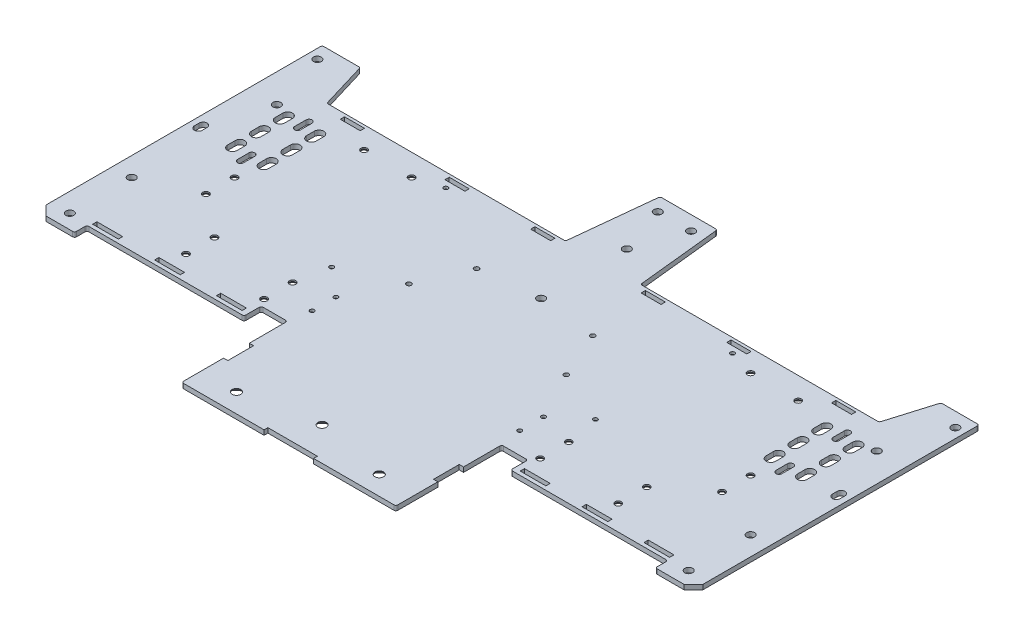
SolidWorks part; units mm, degrees
material "Титан"
ref_plane "Спереди" through (0, 0, 0) normal (0, 0, 1) x (1, 0, 0)
ref_plane "Сверху" through (0, 0, 0) normal (0, 1, 0) x (1, 0, 0)
ref_plane "Справа" through (0, 0, 0) normal (1, 0, 0) x (0, 0, -1)
sketch "Эскиз2" plane through (0, 0, 0) normal (0, 1, 0) x (1, 0, 0)
  line L9 (0, 240.5865) -> (0, -896.1011) construction
  line L10 (112.5, -237) -> (112.5, -330)
  line L11 (112.5, -330) -> (-112.5, -330)
  line L13 (-112.5, -237) -> (-112.5, -330)
  line L14 (-345, -237) -> (-112.5, -237)
  line L30 (-345, -237) -> (-345, 50)
  line L31 (-345, 50) -> (-305, 50)
  line L32 (-305, 50) -> (-290, 0)
  line L33 (-290, 0) -> (290, 0)
  line L34 (305, 50) -> (290, 0)
  line L35 (345, 50) -> (305, 50)
  line L39 (345, -237) -> (345, 50)
  line L40 (112.5, -237) -> (345, -237)
  dimension "D2" = 690
  dimension "D4" = 50
  dimension "D5" = 580
  dimension "D6" = 40
  dimension "D7" = 330
  dimension "D8" = 93
  dimension "D10" = 225
extrude "Бобышка-Вытянуть1" add sketch "Эскиз2" along normal blind 5
sketch "Эскиз21" plane through (0, 5, 0) normal (0, 1, 0) x (1, 0, 0)
  line L0 (-39.4594, 0) -> (-30, 90)
  line L1 (290, 0) -> (-290, 0) construction
  line L2 (0, 0) -> (0, -50000) construction
  line L3 (39.4594, 0) -> (30, 90)
  line L4 (-30, 90) -> (30, 90)
  line L5 (-39.4594, 0) -> (39.4594, 0)
  dimension "D1" = 90
  dimension "D2" = 12
  dimension "D3" = 60
extrude "Бобышка-Вытянуть2" add sketch "Эскиз21" against normal blind 5
sketch "Эскиз22" plane through (0, 5, 0) normal (0, 1, 0) x (1, 0, 0)
  line L0 (0, 0) -> (0, -50000) construction
  line L1 (-345, -237) -> (-305, -237)
  line L2 (-345, -237) -> (-345, -250)
  line L3 (-345, -250) -> (-305, -250)
  line L4 (-305, -237) -> (-305, -250)
  line L5 (305, -237) -> (305, -250)
  line L6 (345, -250) -> (305, -250)
  line L7 (345, -237) -> (345, -250)
  line L8 (345, -237) -> (305, -237)
  line L9 (-345, -237) -> (-112.5, -237) construction
  dimension "D1" = 40
  dimension "D2" = 13
extrude "Бобышка-Вытянуть3" add sketch "Эскиз22" against normal blind 5
sketch "Эскиз8" plane through (0, 5, 0) normal (0, 1, 0) x (1, 0, 0)
  line L0 (-39.4594, 0) -> (-290, 0) construction
  line L3 (-266.25, -40) -> (-266.25, -32) construction
  line L6 (-271.25, -40) -> (-271.25, -32)
  line L9 (-261.25, -40) -> (-261.25, -32)
  line L12 (-266.25, -65) -> (-266.25, -57) construction
  line L19 (-271.25, -65) -> (-271.25, -57)
  line L22 (-261.25, -65) -> (-261.25, -57)
  line L25 (-266.25, -90) -> (-266.25, -82) construction
  line L26 (0, 0) -> (0, -50000) construction
  line L29 (-271.25, -90) -> (-271.25, -82)
  line L38 (-261.25, -90) -> (-261.25, -82)
  line L45 (-299.25, -65) -> (-299.25, -57) construction
  line L46 (-304.25, -65) -> (-304.25, -57)
  line L49 (-299.25, -40) -> (-299.25, -32) construction
  line L50 (-304.25, -40) -> (-304.25, -32)
  line L51 (-294.25, -40) -> (-294.25, -32)
  line L52 (-294.25, -65) -> (-294.25, -57)
  line L53 (-299.25, -90) -> (-299.25, -82) construction
  line L54 (-304.25, -90) -> (-304.25, -82)
  line L55 (-294.25, -90) -> (-294.25, -82)
  line L56 (266.25, -40) -> (266.25, -32) construction
  line L57 (271.25, -40) -> (271.25, -32)
  line L58 (261.25, -40) -> (261.25, -32)
  line L59 (266.25, -65) -> (266.25, -57) construction
  line L60 (271.25, -65) -> (271.25, -57)
  line L61 (261.25, -65) -> (261.25, -57)
  line L62 (266.25, -90) -> (266.25, -82) construction
  line L63 (271.25, -90) -> (271.25, -82)
  line L64 (261.25, -90) -> (261.25, -82)
  line L65 (299.25, -65) -> (299.25, -57) construction
  line L66 (304.25, -65) -> (304.25, -57)
  line L67 (294.25, -65) -> (294.25, -57)
  line L68 (299.25, -40) -> (299.25, -32) construction
  line L69 (304.25, -40) -> (304.25, -32)
  line L70 (294.25, -40) -> (294.25, -32)
  line L71 (299.25, -90) -> (299.25, -82) construction
  line L72 (304.25, -90) -> (304.25, -82)
  line L73 (294.25, -90) -> (294.25, -82)
  arc A36 (-304.25, -40) -> (-294.25, -40) centre (-299.25, -40) ccw
  arc A37 (-294.25, -32) -> (-304.25, -32) centre (-299.25, -32) ccw
  arc A38 (-271.25, -40) -> (-261.25, -40) centre (-266.25, -40) ccw
  arc A39 (-261.25, -32) -> (-271.25, -32) centre (-266.25, -32) ccw
  arc A40 (-271.25, -65) -> (-261.25, -65) centre (-266.25, -65) ccw
  arc A41 (-261.25, -57) -> (-271.25, -57) centre (-266.25, -57) ccw
  arc A42 (-271.25, -90) -> (-261.25, -90) centre (-266.25, -90) ccw
  arc A43 (-261.25, -82) -> (-271.25, -82) centre (-266.25, -82) ccw
  arc A44 (-304.25, -65) -> (-294.25, -65) centre (-299.25, -65) ccw
  arc A45 (-294.25, -57) -> (-304.25, -57) centre (-299.25, -57) ccw
  arc A46 (-304.25, -90) -> (-294.25, -90) centre (-299.25, -90) ccw
  arc A47 (-294.25, -82) -> (-304.25, -82) centre (-299.25, -82) ccw
  arc A48 (271.25, -40) -> (261.25, -40) centre (266.25, -40) cw
  arc A49 (261.25, -32) -> (271.25, -32) centre (266.25, -32) cw
  arc A50 (271.25, -65) -> (261.25, -65) centre (266.25, -65) cw
  arc A51 (261.25, -57) -> (271.25, -57) centre (266.25, -57) cw
  arc A52 (271.25, -90) -> (261.25, -90) centre (266.25, -90) cw
  arc A53 (261.25, -82) -> (271.25, -82) centre (266.25, -82) cw
  arc A54 (304.25, -65) -> (294.25, -65) centre (299.25, -65) cw
  arc A55 (294.25, -57) -> (304.25, -57) centre (299.25, -57) cw
  arc A56 (304.25, -40) -> (294.25, -40) centre (299.25, -40) cw
  arc A57 (294.25, -32) -> (304.25, -32) centre (299.25, -32) cw
  arc A58 (304.25, -90) -> (294.25, -90) centre (299.25, -90) cw
  arc A59 (294.25, -82) -> (304.25, -82) centre (299.25, -82) cw
  point P4 (266.25, -36)
  point P7 (-266.25, -36)
  point P14 (-266.25, -61)
  point P21 (-266.25, -86)
  point P28 (-299.25, -61)
  point P35 (-299.25, -86)
  point P48 (266.25, -61)
  point P55 (266.25, -86)
  point P62 (299.25, -61)
  point P69 (-299.25, -36)
  point P76 (299.25, -36)
  point P83 (299.25, -86)
  dimension "D2" = 8
  dimension "D1" = 10
  dimension "D3" = 598.5
  dimension "D4" = 36
  dimension "D5" = 2
  dimension "D6" = 3
  dimension "D7" = 33
extrude "Вырез-Вытянуть1" cut sketch "Эскиз8" against normal blind 45
sketch "Эскиз11" plane through (0, 5, 0) normal (0, 1, 0) x (1, 0, 0)
  line L0 (-282.75, -38) -> (-282.75, -26) construction
  line L1 (-285.85, -38) -> (-285.85, -26)
  line L2 (-279.65, -38) -> (-279.65, -26)
  line L3 (-282.75, -98) -> (-282.75, -86) construction
  line L4 (-285.85, -98) -> (-285.85, -86)
  line L5 (-279.65, -98) -> (-279.65, -86)
  line L6 (0, -2.75) -> (0, 2.75) construction
  line L7 (282.75, -38) -> (282.75, -26) construction
  line L8 (285.85, -38) -> (285.85, -26)
  line L9 (279.65, -38) -> (279.65, -26)
  line L10 (282.75, -98) -> (282.75, -86) construction
  line L11 (285.85, -98) -> (285.85, -86)
  line L12 (279.65, -98) -> (279.65, -86)
  line L13 (0, 0) -> (0, -50000) construction
  line L14 (-39.4594, 0) -> (-290, 0) construction
  arc A0 (-285.85, -38) -> (-279.65, -38) centre (-282.75, -38) ccw
  arc A1 (-279.65, -26) -> (-285.85, -26) centre (-282.75, -26) ccw
  arc A2 (-285.85, -98) -> (-279.65, -98) centre (-282.75, -98) ccw
  arc A3 (-279.65, -86) -> (-285.85, -86) centre (-282.75, -86) ccw
  arc A4 (285.85, -38) -> (279.65, -38) centre (282.75, -38) cw
  arc A5 (279.65, -26) -> (285.85, -26) centre (282.75, -26) cw
  arc A6 (285.85, -98) -> (279.65, -98) centre (282.75, -98) cw
  arc A7 (279.65, -86) -> (285.85, -86) centre (282.75, -86) cw
  point P2 (-282.75, -32)
  point P10 (-282.75, -92)
  point P20 (282.75, -32)
  point P27 (282.75, -92)
  dimension "D1" = 6.2
  dimension "D2" = 12
  dimension "D3" = 6.2
  dimension "D4" = 12
  dimension "D5" = 565.5
  dimension "D6" = 60
  dimension "D7" = 32
extrude "Вырез-Вытянуть4" cut sketch "Эскиз11" against normal blind 70
sketch "Эскиз23" plane through (0, 5, 0) normal (0, 1, 0) x (1, 0, 0)
  line L0 (-112.5, -237) -> (-112.5, -219)
  line L1 (-112.5, -219) -> (-140, -219)
  line L2 (-140, -219) -> (-140, -237)
  line L3 (-305, -237) -> (-112.5, -237) construction
  line L4 (-140, -237) -> (-112.5, -237)
  line L5 (0, -3.1169) -> (0, -50003.1169) construction
  line L6 (140, -237) -> (112.5, -237)
  line L7 (140, -219) -> (140, -237)
  line L8 (112.5, -219) -> (140, -219)
  line L9 (112.5, -237) -> (112.5, -219)
  dimension "D1" = 18
  dimension "D2" = 27.5
extrude "Вырез-Вытянуть6" cut sketch "Эскиз23" against normal blind 10
sketch "Эскиз26" plane through (0, 0, 0) normal (0, 1, 0) x (1, 0, 0)
  line L0 (-39.4594, 0) -> (-290, 0) construction
  line L1 (-228, -23) -> (49772, -23) construction
  line L2 (0, 0) -> (0, -50000) construction
  point P0 (-228, -23)
  point P12 (-178, -23)
  point P15 (178, -23)
  point P16 (228, -23)
  dimension "D1" = 23
  dimension "D2" = 50
  dimension "D3" = 356
sketch "Эскиз27" plane through (0, 5, 0) normal (0, 1, 0) x (1, 0, 0)
  line L0 (-39.4594, 0) -> (-290, 0) construction
  line L1 (-268.5, -3) -> (-247.5, -3)
  line L2 (-268.5, -3) -> (-268.5, -7.5)
  line L3 (-268.5, -7.5) -> (-247.5, -7.5)
  line L4 (-247.5, -3) -> (-247.5, -7.5)
  line L5 (0, 0) -> (0, -50000) construction
  line L6 (-158.5, -3) -> (-137.5, -3)
  line L7 (-158.5, -3) -> (-158.5, -7.5)
  line L8 (-158.5, -7.5) -> (-137.5, -7.5)
  line L9 (-137.5, -3) -> (-137.5, -7.5)
  line L10 (-68.5, -3) -> (-47.5, -3)
  line L11 (-68.5, -3) -> (-68.5, -7.5)
  line L12 (-68.5, -7.5) -> (-47.5, -7.5)
  line L13 (-47.5, -3) -> (-47.5, -7.5)
  line L14 (47.5, -3) -> (47.5, -7.5)
  line L15 (68.5, -7.5) -> (47.5, -7.5)
  line L16 (68.5, -3) -> (68.5, -7.5)
  line L17 (68.5, -3) -> (47.5, -3)
  line L18 (137.5, -3) -> (137.5, -7.5)
  line L19 (158.5, -7.5) -> (137.5, -7.5)
  line L20 (158.5, -3) -> (158.5, -7.5)
  line L21 (158.5, -3) -> (137.5, -3)
  line L22 (247.5, -3) -> (247.5, -7.5)
  line L23 (268.5, -7.5) -> (247.5, -7.5)
  line L24 (268.5, -3) -> (268.5, -7.5)
  line L25 (268.5, -3) -> (247.5, -3)
  dimension "D1" = 3
  dimension "D2" = 21
  dimension "D3" = 4.5
  dimension "D5" = 537
  dimension "D6" = 110
  dimension "D7" = 4.5
  dimension "D4" = 90
  dimension "D8" = 4.5
extrude "Вырез-Вытянуть7" cut sketch "Эскиз27" against normal through all
sketch "Эскиз38" plane through (0, 5, 0) normal (0, 1, 0) x (1, 0, 0)
  line L0 (-140, -219) -> (-140, -237) construction
  line L1 (-146, -233) -> (-173, -233)
  line L2 (-146, -233) -> (-146, -228.5)
  line L3 (-146, -228.5) -> (-173, -228.5)
  line L4 (-173, -233) -> (-173, -228.5)
  line L5 (-305, -237) -> (-140, -237) construction
  line L6 (-171, -233) -> (-50171, -233) construction
  line L7 (-171, -228.5) -> (-50171, -228.5) construction
  line L8 (0, 0) -> (0, -50000) construction
  line L9 (-211, -233) -> (-238, -233)
  line L10 (-211, -233) -> (-211, -228.5)
  line L11 (-211, -228.5) -> (-238, -228.5)
  line L12 (-238, -233) -> (-238, -228.5)
  line L13 (-276, -233) -> (-303, -233)
  line L14 (-276, -233) -> (-276, -228.5)
  line L15 (-276, -228.5) -> (-303, -228.5)
  line L16 (-303, -233) -> (-303, -228.5)
  line L17 (303, -233) -> (303, -228.5)
  line L18 (276, -228.5) -> (303, -228.5)
  line L19 (276, -233) -> (276, -228.5)
  line L20 (276, -233) -> (303, -233)
  line L21 (238, -233) -> (238, -228.5)
  line L22 (211, -228.5) -> (238, -228.5)
  line L23 (211, -233) -> (211, -228.5)
  line L24 (211, -233) -> (238, -233)
  line L25 (173, -233) -> (173, -228.5)
  line L26 (146, -228.5) -> (173, -228.5)
  line L27 (146, -233) -> (146, -228.5)
  line L28 (146, -233) -> (173, -233)
  line L29 (-112.5, -219) -> (-112.5, -330) construction
  line L30 (-112.5, -259) -> (-108, -259)
  line L31 (-112.5, -259) -> (-112.5, -286)
  line L32 (-112.5, -286) -> (-108, -286)
  line L33 (-108, -259) -> (-108, -286)
  line L34 (-112.5, -330) -> (112.5, -330) construction
  line L35 (108, -259) -> (108, -286)
  line L36 (112.5, -286) -> (108, -286)
  line L37 (112.5, -259) -> (112.5, -286)
  line L38 (112.5, -259) -> (108, -259)
  line L39 (-112.5, -330) -> (112.5, -330) construction
  line L40 (-26, -330) -> (26, -330)
  line L41 (-26, -330) -> (-26, -326)
  line L42 (-26, -326) -> (26, -326)
  line L43 (26, -330) -> (26, -326)
  dimension "D1" = 6
  dimension "D2" = 4
  dimension "D3" = 27
  dimension "D4" = 4.5
  dimension "D5" = 65
  dimension "D6" = 65
  dimension "D7" = 4.5
  dimension "D8" = 44
  dimension "D9" = 27
  dimension "D10" = 52
  dimension "D11" = 4
extrude "Вырез-Вытянуть8" cut sketch "Эскиз38" against normal through all
hole_wizard "Зенковка для винта с потайной головкой и внутренним шестигранником M61" positions "Эскиз26" profile "Эскиз25" countersink size "M6" standard "DIN" end condition through all
sketch "Эскиз25" plane through (-228, 0, 23) normal (1, 0, 0) x (0, 0, -1)
  line L0 (0, 0) -> (0, 5)
  line L1 (0, 5) -> (3.3, 5)
  line L2 (3.3, 5) -> (3.3, 3.555)
  line L3 (3.3, 3.555) -> (6.855, 0)
  line L5 (6.855, 0) -> (0, 0)
  line L6 (-3.3, 3.555) -> (-6.855, 0) construction
  line L11 (0, -6.35) -> (0, 107.95) construction
  dimension "Диаметр сквозного отверстия" = 6.6
  dimension "Глубина сквозного отверстия" = 5
  dimension "Диаметр передней зенковки" = 13.71
  dimension "Угол передней зенковки" = 90
sketch "Эскиз30" plane through (0, 0, 0) normal (0, 1, 0) x (1, 0, 0)
  line L0 (-39.4594, 0) -> (-290, 0) construction
  line L1 (0, 0) -> (0, -50000) construction
  point P0 (-150.5, -14.5)
  point P10 (150.5, -14.5)
  point P11 (-138.5, -146.5)
  point P14 (138.5, -146.5)
  dimension "D1" = 14.5
  dimension "D2" = 301
  dimension "D3" = 132
  dimension "D4" = 277
hole_wizard "Зенковка для винта с потайной головкой и внутренним шестигранником M41" positions "Эскиз30" profile "Эскиз29" countersink size "M4" standard "DIN" end condition through all
sketch "Эскиз29" plane through (-150.5, 0, 14.5) normal (1, 0, 0) x (0, 0, -1)
  line L0 (0, 0) -> (0, 5)
  line L1 (0, 5) -> (2.25, 5)
  line L2 (2.25, 5) -> (2.25, 2.34)
  line L3 (2.25, 2.34) -> (4.59, 0)
  line L5 (4.59, 0) -> (0, 0)
  line L6 (-2.25, 2.34) -> (-4.59, 0) construction
  line L11 (0, -6.35) -> (0, 107.95) construction
  dimension "Диаметр сквозного отверстия" = 4.5
  dimension "Глубина сквозного отверстия" = 5
  dimension "Диаметр передней зенковки" = 9.18
  dimension "Угол передней зенковки" = 90
sketch "Эскиз33" plane through (0, 0, 0) normal (0, 1, 0) x (1, 0, 0)
  line L0 (-305, 50) -> (-345, 50) construction
  line L1 (-345, 50) -> (-345, -250) construction
  line L2 (0, 0) -> (0, -50000) construction
  line L3 (30, 90) -> (-30, 90) construction
  line L4 (-325, -235) -> (-325, 49765) construction
  line L5 (325, -235) -> (325, 49765) construction
  point P0 (-335, 35)
  point P7 (-315, -27.5)
  point P9 (-335, -85)
  point P11 (-325, -235)
  point P24 (325, -235)
  point P25 (335, -85)
  point P26 (315, -27.5)
  point P27 (335, 35)
  point P28 (-17.5, 75)
  point P31 (0, 25)
  point P33 (0, -65)
  point P39 (17.5, 75)
  point P45 (-325, -170)
  point P48 (325, -170)
  dimension "D1" = 15
  dimension "D2" = 10
  dimension "D3" = 120
  dimension "D4" = 62.5
  dimension "D5" = 20
  dimension "D6" = 270
  dimension "D7" = 20
  dimension "D8" = 15
  dimension "D9" = 50
  dimension "D10" = 90
  dimension "D11" = 35
  dimension "D12" = 65
hole_wizard "Сверло под метчик  спиральное M82" positions "Эскиз33" profile "Эскиз32" hole size "M8x1.0" standard "DIN" end condition through all
sketch "Эскиз32" plane through (-335, 0, -35) normal (1, 0, 0) x (0, 0, -1)
  line L0 (0, 0) -> (0, 5)
  line L1 (0, 5) -> (4.125, 5)
  line L2 (4.125, 5) -> (4.125, 0)
  line L5 (4.125, 0) -> (0, 0)
  line L11 (0, -6.35) -> (0, 107.95) construction
  dimension "Диаметр сквозного отверстия" = 8.25
  dimension "Глубина сквозного отверстия" = 5
sketch "Эскиз36" plane through (0, 0, 0) normal (0, -1, 0) x (-1, 0, 0)
  line L0 (0, 0) -> (0, -50000) construction
  line L1 (-26, -330) -> (-112.5, -330) construction
  point P0 (-75, -310)
  point P2 (75, -310)
  point P9 (0, -295)
  dimension "D1" = 20
  dimension "D2" = 15
  dimension "D3" = 150
hole_wizard "Зенковка для винта с потайной головкой и внутренним шестигранником M82" positions "Эскиз36" profile "Эскиз35" countersink size "M8" standard "DIN" end condition up to next
sketch "Эскиз35" plane through (75, 0, 310) normal (1, 0, 0) x (0, 0, -1)
  line L0 (0, 0) -> (0, 5)
  line L1 (0, 5) -> (4.5, 5)
  line L2 (4.5, 5) -> (4.5, 4.625)
  line L3 (4.5, 4.625) -> (9.125, 0)
  line L5 (9.125, 0) -> (0, 0)
  line L6 (-4.5, 4.625) -> (-9.125, 0) construction
  line L11 (0, -6.35) -> (0, 107.95) construction
  dimension "Диаметр сквозного отверстия" = 9
  dimension "Глубина сквозного отверстия" = 5
  dimension "Диаметр передней зенковки" = 18.25
  dimension "Угол передней зенковки" = 90
sketch "Эскиз41" plane through (0, 0, 0) normal (0, -1, 0) x (-1, 0, 0)
  line L0 (0, 0) -> (0, -50000) construction
  line L1 (-140, -237) -> (-305, -237) construction
  point P0 (-227, -211)
  point P7 (227, -211)
  point P10 (-227, -181)
  point P12 (227, -181)
  point P19 (-271, -146)
  point P21 (-271, -116)
  point P24 (271, -116)
  point P25 (271, -146)
  point P26 (-145, -181)
  point P28 (-145, -211)
  point P34 (145, -211)
  point P35 (145, -181)
  dimension "D1" = 454
  dimension "D2" = 26
  dimension "D3" = 30
  dimension "D4" = 542
  dimension "D5" = 91
  dimension "D6" = 30
  dimension "D7" = 82
hole_wizard "Зенковка для винта с потайной головкой и внутренним шестигранником M62" positions "Эскиз41" profile "Эскиз40" countersink size "M6" standard "DIN"
sketch "Эскиз40" plane through (227, 0, 211) normal (1, 0, 0) x (0, 0, -1)
  line L0 (0, 0) -> (0, 18.9828)
  line L1 (0, 18.9828) -> (3.3, 17)
  line L2 (3.3, 17) -> (3.3, 3.555)
  line L3 (3.3, 3.555) -> (6.855, 0)
  line L5 (6.855, 0) -> (0, 0)
  line L6 (-3.3, 3.555) -> (-6.855, 0) construction
  line L10 (0, 18.9828) -> (-3.3, 17) construction
  line L11 (0, -6.35) -> (0, 107.95) construction
  dimension "Диаметр отверстия" = 6.6
  dimension "Глубина отверстия" = 17
  dimension "Диаметр передней зенковки" = 13.71
  dimension "Угол передней зенковки" = 90
  dimension "Угол заточки сверла" = 118
sketch "Эскиз44" plane through (0, 0, 0) normal (0, -1, 0) x (-1, 0, 0)
  line L0 (0, 0) -> (0, -50000) construction
  line L1 (-109, -172.415) -> (-109, -50172.415) construction
  line L2 (-290, 0) -> (-39.4594, 0) construction
  point P0 (-109, -171.5)
  point P10 (-109, -196.5)
  point P13 (109, -196.5)
  point P14 (109, -171.5)
  dimension "D1" = 25
  dimension "D2" = 171.5
  dimension "D3" = 218
hole_wizard "Зенковка для винта с потайной головкой и внутренним шестигранником M42" positions "Эскиз44" profile "Эскиз43" countersink size "M4" standard "DIN" end condition through all
sketch "Эскиз43" plane through (109, 0, 171.5) normal (1, 0, 0) x (0, 0, -1)
  line L0 (0, 0) -> (0, 5)
  line L1 (0, 5) -> (2.25, 5)
  line L2 (2.25, 5) -> (2.25, 2.34)
  line L3 (2.25, 2.34) -> (4.59, 0)
  line L5 (4.59, 0) -> (0, 0)
  line L6 (-2.25, 2.34) -> (-4.59, 0) construction
  line L11 (0, -6.35) -> (0, 107.95) construction
  dimension "Диаметр сквозного отверстия" = 4.5
  dimension "Глубина сквозного отверстия" = 5
  dimension "Диаметр передней зенковки" = 9.18
  dimension "Угол передней зенковки" = 90
sketch "Эскиз45" plane through (0, 0, 0) normal (0, -1, 0) x (1, 0, 0)
  line L0 (-335, 85) -> (-335, 90) construction
  line L1 (-339.125, 90) -> (-339.125, 85)
  line L2 (-330.875, 90) -> (-330.875, 85)
  line L3 (-339.125, 85) -> (-330.875, 85)
  line L4 (0, 0) -> (0, 131.6943) construction
  line L5 (-339.125, 90) -> (-339.125, 85)
  line L6 (-330.875, 90) -> (-330.875, 85)
  line L7 (-339.125, 90) -> (-339.125, 85)
  line L8 (-330.875, 90) -> (-330.875, 85)
  line L9 (-339.125, 90) -> (-339.125, 85)
  line L10 (-330.875, 90) -> (-330.875, 85)
  line L11 (335, 85) -> (335, 90) construction
  line L12 (330.875, 90) -> (330.875, 85)
  line L13 (339.125, 90) -> (339.125, 85)
  line L14 (330.875, 90) -> (330.875, 85)
  line L15 (339.125, 90) -> (339.125, 85)
  line L16 (330.875, 90) -> (330.875, 85)
  line L17 (339.125, 90) -> (339.125, 85)
  line L18 (339.125, 85) -> (330.875, 85)
  line L19 (330.875, 90) -> (330.875, 85)
  line L20 (339.125, 90) -> (339.125, 85)
  circle A1 centre (-335, 85) radius 4.125 construction
  circle A2 centre (-335, 85) radius 4.125 construction
  circle A4 centre (335, 85) radius 4.125 construction
  arc A6 (-330.875, 90) -> (-339.125, 90) centre (-335, 90) ccw
  arc A7 (330.875, 90) -> (339.125, 90) centre (335, 90) cw
  dimension "D1" = 5
extrude "Вырез-Вытянуть10" cut sketch "Эскиз45" against normal through all
chamfer "Фаска1" distance 10 angle 45 2 edges at (-345, 2.5, 250) (345, 2.5, 250)
fillet "Скругление1" radius 2 22 edges at (-345, 2.5, -50) (-305, 2.5, -50) (-290, 2.5, 0) (39.4594, 2.5, 0) (-39.4594, 2.5, 0) (30, 2.5, -90) (-30, 2.5, -90) (345, 2.5, -50) (305, 2.5, -50) (290, 2.5, 0) (305, 2.5, 237) (305, 2.5, 250) (-305, 2.5, 237) (-305, 2.5, 250) (-112.5, 2.5, 219) (-140, 2.5, 219) (-140, 2.5, 237) (140, 2.5, 237) (140, 2.5, 219) (112.5, 2.5, 219) (112.5, 2.5, 330) (-112.5, 2.5, 330)
sketch "Эскиз46" plane through (0, 5, 0) normal (0, 1, 0) x (1, 0, 0)
  line L0 (0, -79) -> (0, -126.3453) construction
  circle A0 centre (82.67, -121.2) radius 2.5
  circle A1 centre (60.9905, -71.7822) radius 2.5
  circle A2 centre (-60.9905, -71.7822) radius 2.5
  circle A3 centre (-82.67, -121.2) radius 2.5
extrude "Вырез-Вытянуть11" cut sketch "Эскиз46" against normal through all
